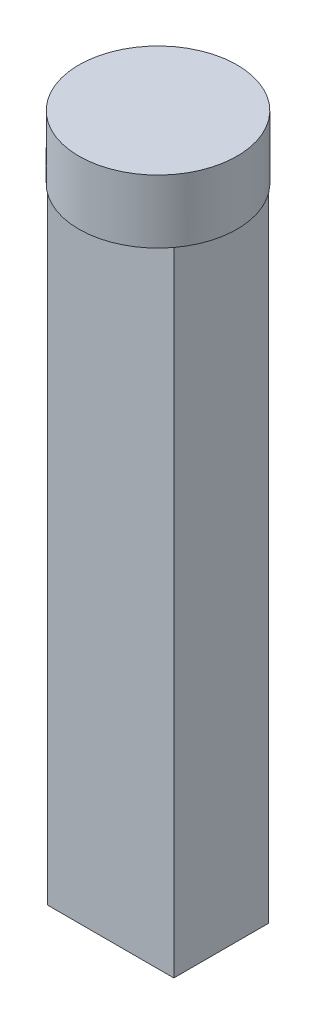
SolidWorks part; units mm, degrees
material "1060-H18 Rod (SS)"
ref_plane "Front Plane" through (0, 0, 0) normal (0, 0, 1) x (1, 0, 0)
ref_plane "Top Plane" through (0, 0, 0) normal (0, 1, 0) x (1, 0, 0)
ref_plane "Right Plane" through (0, 0, 0) normal (1, 0, 0) x (0, 0, -1)
sketch "Sketch1" plane through (0, 0, 0) normal (0, 1, 0) x (1, 0, 0)
  line L1 (10, -7.5) -> (-10, -7.5)
  line L2 (10, -7.5) -> (10, 7.5)
  line L3 (10, 7.5) -> (-10, 7.5)
  line L4 (-10, -7.5) -> (-10, 7.5)
  line L5 (10, -7.5) -> (-10, 7.5) construction
  line L6 (10, 7.5) -> (-10, -7.5) construction
  point P0 (0, 0)
  dimension "D1" = 15
  dimension "D2" = 20
extrude "Boss-Extrude1" add sketch "Sketch1" along normal blind 100
sketch "Sketch2" plane through (0, 100, 0) normal (0, 1, 0) x (1, 0, 0)
  circle A0 centre (0, 0) radius 12.5
extrude "Boss-Extrude2" add sketch "Sketch2" along normal blind 10
